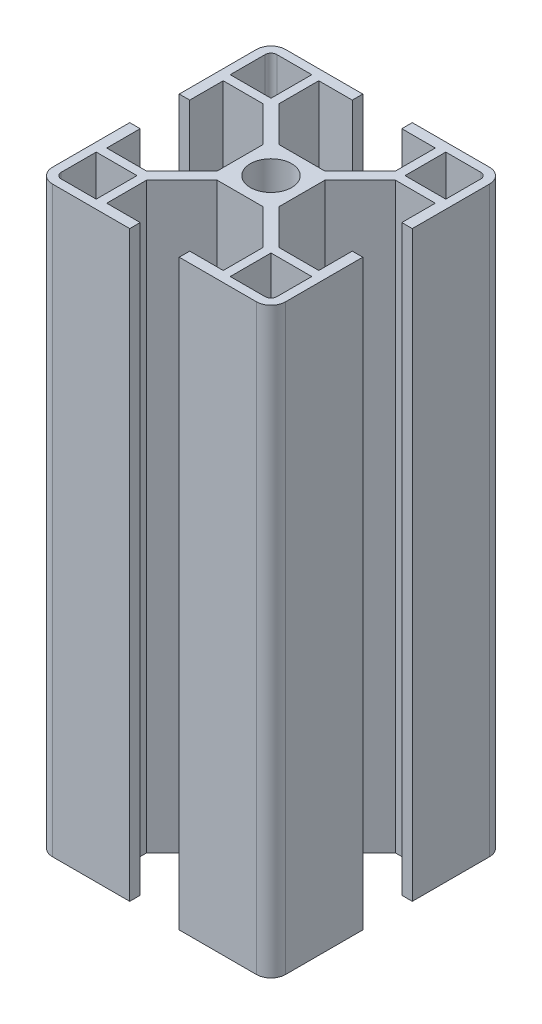
SolidWorks part; units mm, degrees
ref_plane "前视基准面" through (0, 0, 0) normal (0, 0, 1) x (1, 0, 0)
ref_plane "上视基准面" through (0, 0, 0) normal (0, 1, 0) x (1, 0, 0)
ref_plane "右视基准面" through (0, 0, 0) normal (1, 0, 0) x (0, 0, -1)
other "Configuration Table"
sketch "草图1" plane through (0, 0, 0) normal (0, 1, 0) x (1, 0, 0)
  line L0 (-28.4403, 0) -> (36.2792, 0) construction
  line L1 (0, 26.4889) -> (0, -19.5972) construction
  line L2 (0, 0) -> (-20.5491, 20.5491) construction
  line L3 (-20, 20) -> (-4.25, 20)
  line L4 (-4.25, 20) -> (-4.25, 18.2)
  line L5 (-4.25, 18.2) -> (-10, 18.2)
  line L6 (-10, 18.2) -> (-10, 11.3435)
  line L7 (-18.5, 18.5) -> (-11.5, 18.5)
  line L8 (-11.5, 18.5) -> (-11.5, 11.5)
  line L9 (-10, 11.3435) -> (-3.9565, 5.3)
  line L10 (-3.9565, 5.3) -> (3.9565, 5.3)
  line L11 (-5.3, 3.9565) -> (-5.3, -3.9565)
  line L12 (-11.3435, 10) -> (-5.3, 3.9565)
  line L13 (-18.5, 11.5) -> (-11.5, 11.5)
  line L14 (-18.5, 18.5) -> (-18.5, 11.5)
  line L15 (-18.2, 10) -> (-11.3435, 10)
  line L16 (-18.2, 4.25) -> (-18.2, 10)
  line L17 (-20, 4.25) -> (-18.2, 4.25)
  line L18 (-20, 20) -> (-20, 4.25)
  line L19 (20, 20) -> (20, 4.25)
  line L20 (20, 4.25) -> (18.2, 4.25)
  line L21 (18.2, 4.25) -> (18.2, 10)
  line L22 (18.2, 10) -> (11.3435, 10)
  line L23 (18.5, 18.5) -> (18.5, 11.5)
  line L24 (18.5, 11.5) -> (11.5, 11.5)
  line L25 (11.3435, 10) -> (5.3, 3.9565)
  line L26 (5.3, 3.9565) -> (5.3, -3.9565)
  line L27 (10, 11.3435) -> (3.9565, 5.3)
  line L28 (11.5, 18.5) -> (11.5, 11.5)
  line L29 (18.5, 18.5) -> (11.5, 18.5)
  line L30 (10, 18.2) -> (10, 11.3435)
  line L31 (4.25, 18.2) -> (10, 18.2)
  line L32 (4.25, 20) -> (4.25, 18.2)
  line L33 (20, 20) -> (4.25, 20)
  line L34 (0, -26.4889) -> (0, 19.5972) construction
  line L35 (20, -20) -> (4.25, -20)
  line L36 (4.25, -20) -> (4.25, -18.2)
  line L37 (4.25, -18.2) -> (10, -18.2)
  line L38 (10, -18.2) -> (10, -11.3435)
  line L39 (18.5, -18.5) -> (11.5, -18.5)
  line L40 (11.5, -18.5) -> (11.5, -11.5)
  line L41 (10, -11.3435) -> (3.9565, -5.3)
  line L42 (11.3435, -10) -> (5.3, -3.9565)
  line L43 (18.5, -11.5) -> (11.5, -11.5)
  line L44 (18.5, -18.5) -> (18.5, -11.5)
  line L45 (18.2, -10) -> (11.3435, -10)
  line L46 (18.2, -4.25) -> (18.2, -10)
  line L47 (20, -4.25) -> (18.2, -4.25)
  line L48 (20, -20) -> (20, -4.25)
  line L49 (-20, -20) -> (-20, -4.25)
  line L50 (-20, -4.25) -> (-18.2, -4.25)
  line L51 (-18.2, -4.25) -> (-18.2, -10)
  line L52 (-18.2, -10) -> (-11.3435, -10)
  line L53 (-18.5, -18.5) -> (-18.5, -11.5)
  line L54 (-18.5, -11.5) -> (-11.5, -11.5)
  line L55 (-11.3435, -10) -> (-5.3, -3.9565)
  line L56 (-3.9565, -5.3) -> (3.9565, -5.3)
  line L57 (-10, -11.3435) -> (-3.9565, -5.3)
  line L58 (-11.5, -18.5) -> (-11.5, -11.5)
  line L59 (-18.5, -18.5) -> (-11.5, -18.5)
  line L60 (-10, -18.2) -> (-10, -11.3435)
  line L61 (-4.25, -18.2) -> (-10, -18.2)
  line L62 (-4.25, -20) -> (-4.25, -18.2)
  line L63 (-20, -20) -> (-4.25, -20)
  circle A0 centre (0, 0) radius 3.55
  point P37 (0, 5.3)
  point P53 (5.3, 0)
  point P67 (-5.3, 0)
  point P73 (0, -5.3)
  dimension "D9" = 3.55
  dimension "D1" = 20
  dimension "D3" = 1.5
  dimension "D4" = 1.8
  dimension "D5" = 4.25
  dimension "D6" = 1.9
  dimension "D7" = 10
  dimension "D8" = 5.3
  dimension "D10" = 1.5
extrude "凸台-拉伸1" add sketch "草图1" along normal blind 100
fillet "圆角1" radius 1 4 edges at (18.5, 50, -18.5) (-18.5, 50, -18.5) (-18.5, 50, 18.5) (18.5, 50, 18.5)
fillet "圆角2" radius 2.5 4 edges at (-20, 50, 20) (20, 50, 20) (20, 50, -20) (-20, 50, -20)
